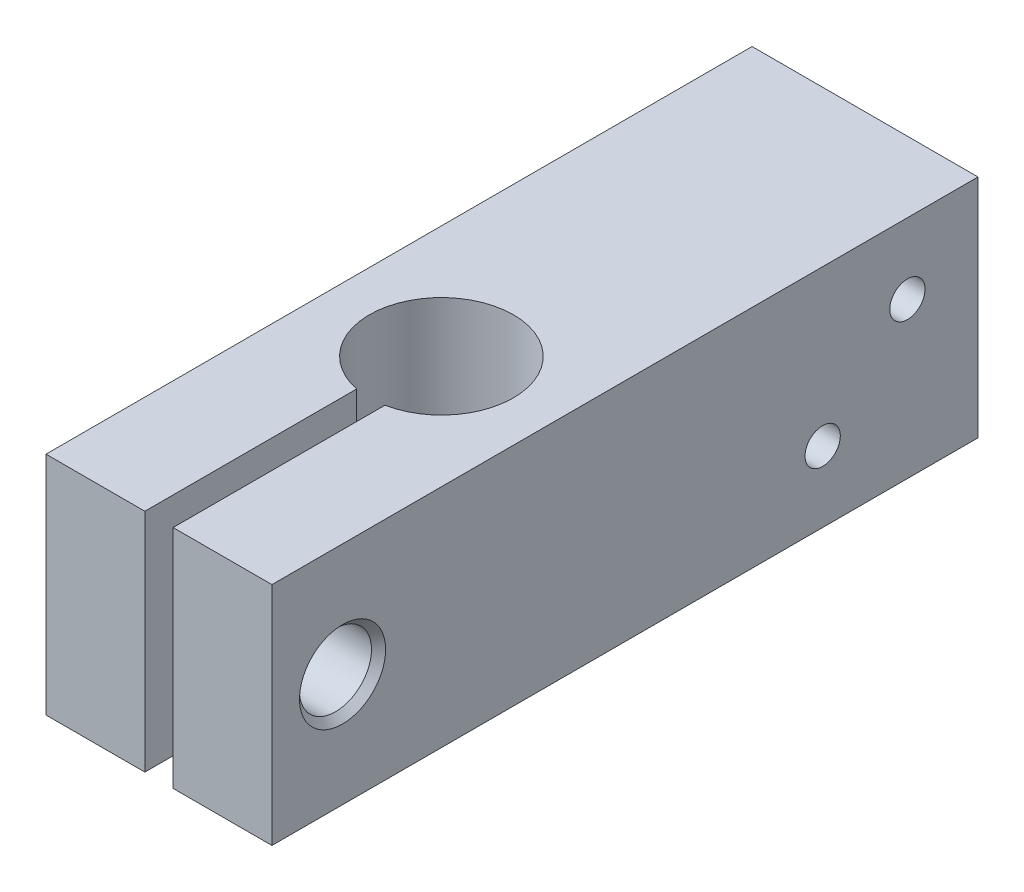
SolidWorks part; units mm, degrees
material "6063-T6"
ref_plane "Front Plane" through (0, 0, 0) normal (0, 0, 1) x (1, 0, 0)
ref_plane "Top Plane" through (0, 0, 0) normal (0, 1, 0) x (1, 0, 0)
ref_plane "Right Plane" through (0, 0, 0) normal (1, 0, 0) x (0, 0, -1)
sketch "Sketch1" plane through (0, 0, 0) normal (0, 0, 1) x (1, 0, 0)
  line L1 (8, -8) -> (-8, -8)
  line L2 (8, -8) -> (8, 8)
  line L3 (8, 8) -> (-8, 8)
  line L4 (-8, -8) -> (-8, 8)
  line L5 (8, -8) -> (-8, 8) construction
  line L6 (8, 8) -> (-8, -8) construction
  point P0 (0, 0)
  dimension "D1" = 16
  dimension "D2" = 16
extrude "Base" add sketch "Sketch1" along normal blind 50
sketch "Sketch2" plane through (0, 8, 0) normal (0, 1, 0) x (1, 0, 0)
  line L0 (-1, -50) -> (-1, -34)
  line L1 (8, -50) -> (-8, -50) construction
  line L2 (1, -50) -> (1, -34)
  line L3 (0, 0) -> (0, -9.2456) construction
  line L4 (-1, -34) -> (1, -34)
  dimension "D1" = 16
  dimension "D3" = 2
extrude "RodSlot" cut sketch "Sketch2" against normal through all
hole_wizard "Ø5.1 (5.1) free hole for screw" positions "Sketch7" profile "Sketch8" hole size "Ø5.1" standard "ANSI Metric"
sketch "Sketch7" plane through (8, 0, 0) normal (1, 0, 0) x (0, 0, -1)
  line L0 (-50, -8) -> (-50, 8) construction
  point P0 (-45, 0)
  dimension "D1" = 5
sketch "Sketch8" plane through (8, 0, 45) normal (0, 1, 0) x (0, 0, -1)
  line L0 (0, 0) -> (0, 8.5562)
  line L1 (0, 8.5562) -> (2.55, 7.5)
  line L2 (2.55, 7.5) -> (2.55, 0.5)
  line L3 (2.55, 0.5) -> (3.05, 0)
  line L5 (3.05, 0) -> (0, 0)
  line L6 (-2.55, 0.5) -> (-3.05, 0) construction
  line L10 (0, 8.5562) -> (-2.55, 7.5) construction
  line L11 (0, -6.35) -> (0, 107.95) construction
  dimension "Hole Dia." = 5.1
  dimension "Hole Depth" = 7.5
  dimension "Near C'Sink Dia." = 6.1
  dimension "Near C'Sink Angle" = 90
  dimension "Drill Angle" = 135
hole_wizard "M5x0.8 Tapped Hole for rod screw" positions "Sketch4" profile "Sketch5" tap size "M5x0.8" standard "ANSI Metric"
sketch "Sketch4" plane through (-8, 0, 0) normal (-1, 0, 0) x (0, 0, 1)
  point P0 (45, 0)
cosmetic thread "Hole Thread1" parameters "D1"=7, "D2"=5
sketch "Sketch5" plane through (-8, 0, 45) normal (0, 1, 0) x (0, 0, 1)
  line L0 (0, 0) -> (0, 8.9)
  line L1 (0, 8.9) -> (2.1, 7.6382)
  line L2 (2.1, 7.6382) -> (2.1, 0)
  line L5 (2.1, 0) -> (0, 0)
  line L10 (0, 8.9) -> (-2.1, 7.6382) construction
  line L11 (0, -6.35) -> (0, 107.95) construction
  dimension "Tap Drill Dia." = 4.2
  dimension "Tap Drill Depth" = 8.9
  dimension "Drill Angle" = 118
hole_wizard "Ø3.1 (3.1) screw holes" positions "Sketch9" profile "Sketch10" tap size "M3x0.5" standard "ANSI Metric" end condition through all
sketch "Sketch9" plane through (8, 0, 0) normal (-1, 0, 0) x (0, 1, 0)
  line L1 (-8, -50) -> (-8, 0) construction
  line L3 (8, 0) -> (-8, 0) construction
  point P0 (3, -5)
  point P2 (-3, -11)
  point P11 (-7.3224, 0)
  point P18 (-4.0308, 0)
  point P21 (-5.3227, -7.8989)
  point P24 (-7.064, 0)
  dimension "D1" = 11
  dimension "D2" = 5
  dimension "D3" = 11
  dimension "D4" = 5
sketch "Sketch10" plane through (8, 3, 5) normal (0, 1, 0) x (0, 0, -1)
  line L0 (0, 0) -> (0, 16)
  line L1 (0, 16) -> (1.25, 16)
  line L2 (1.25, 16) -> (1.25, 0)
  line L5 (1.25, 0) -> (0, 0)
  line L11 (0, -6.35) -> (0, 107.95) construction
  dimension "Thru Tap Drill Dia." = 2.5
  dimension "Thru Tap Drill Depth" = 16
cosmetic thread "Hole Thread2" parameters "D2"=3
cosmetic thread "Hole Thread3" parameters "D2"=3
hole_wizard "Ø10.2 (10.2) Rod Hole" positions "Sketch11" profile "Sketch12" hole size "Ø10.2" standard "ANSI Metric" end condition through all
sketch "Sketch11" plane through (0, 8, 0) normal (0, 1, 0) x (1, 0, 0)
  line L1 (8, -50) -> (1, -50) construction
  point P0 (0, -30)
  dimension "D1" = 20
sketch "Sketch12" plane through (0, 8, 30) normal (1, 0, 0) x (0, 0, 1)
  line L0 (0, 0) -> (0, 16)
  line L1 (0, 16) -> (5.1, 16)
  line L2 (5.1, 16) -> (5.1, 0)
  line L5 (5.1, 0) -> (0, 0)
  line L11 (0, -6.35) -> (0, 107.95) construction
  dimension "Thru Hole Dia." = 10.2
  dimension "Thru Hole Depth" = 16
equation "\"D2@Sketch1\"=\"D1@Sketch1\""
